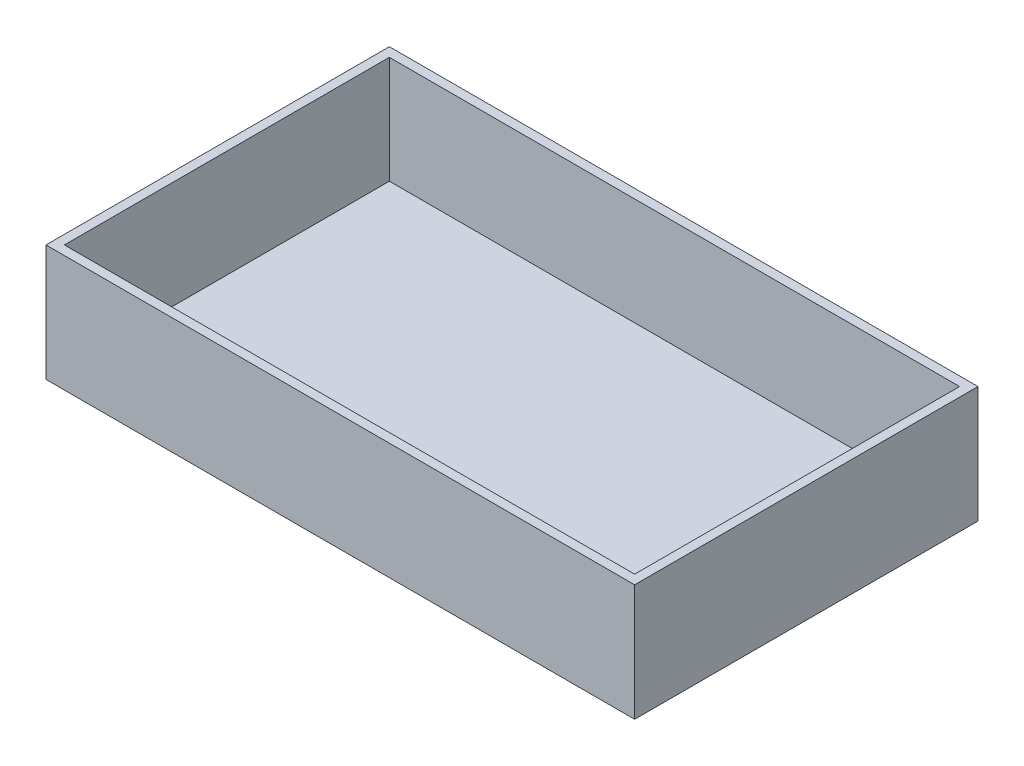
SolidWorks part; units mm, degrees
ref_plane "Front Plane" through (0, 0, 0) normal (0, 0, 1) x (1, 0, 0)
ref_plane "Top Plane" through (0, 0, 0) normal (0, 1, 0) x (1, 0, 0)
ref_plane "Right Plane" through (0, 0, 0) normal (1, 0, 0) x (0, 0, -1)
sketch "Sketch1" plane through (0, 0, 0) normal (0, 1, 0) x (1, 0, 0)
  line L1 (48, 28) -> (-48, 28)
  line L2 (48, 28) -> (48, -28)
  line L3 (48, -28) -> (-48, -28)
  line L4 (-48, 28) -> (-48, -28)
  line L5 (48, 28) -> (-48, -28) construction
  line L6 (48, -28) -> (-48, 28) construction
  point P0 (0, 0)
  dimension "D1" = 96
  dimension "D2" = 56
extrude "Boss-Extrude1" add sketch "Sketch1" along normal blind 19
shell "Shell1" thickness 1.5
sketch "Sketch2" plane through (0, 1.5, 0) normal (0, 1, 0) x (1, 0, 0)
  line L0 (-40.348, 26.5) -> (-40.348, -23.5) construction
  line L1 (46.5, 26.5) -> (-46.5, 26.5) construction
  line L2 (46.5, -26.5) -> (46.5, 26.5) construction
  line L3 (1, -23.5) -> (-34.5, -23.5)
  line L4 (1, -23.5) -> (1, -15.5)
  line L5 (1, -15.5) -> (-34.5, -15.5)
  line L6 (-34.5, -23.5) -> (-34.5, -15.5)
  dimension "D1" = 50
  dimension "D2" = 8
  dimension "D3" = 45.5
  dimension "D4" = 81
extrude "Cut-Extrude2" cut sketch "Sketch2" against normal blind 19
